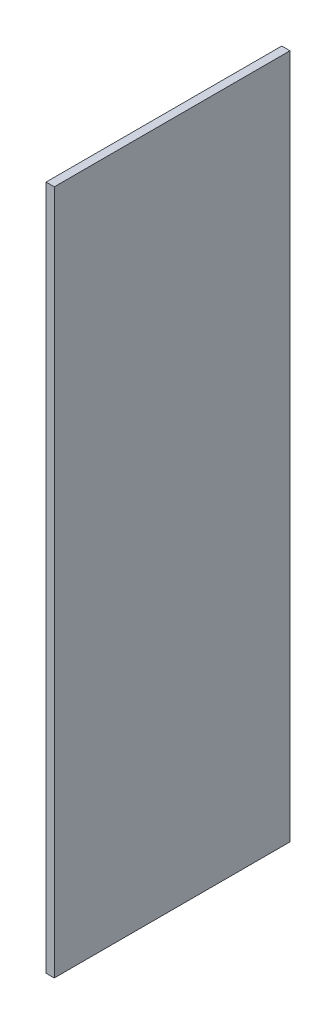
SolidWorks part; units mm, degrees
ref_plane "정면" through (0, 0, 0) normal (0, 0, 1) x (1, 0, 0)
ref_plane "윗면" through (0, 0, 0) normal (0, 1, 0) x (1, 0, 0)
ref_plane "우측면" through (0, 0, 0) normal (1, 0, 0) x (0, 0, -1)
sketch "스케치1" plane through (0, 0, 0) normal (1, 0, 0) x (0, 0, -1)
  line L1 (0, 0) -> (86, 0)
  line L2 (0, 0) -> (0, 250)
  line L3 (0, 250) -> (86, 250)
  line L4 (86, 0) -> (86, 250)
  dimension "D1" = 86
  dimension "D2" = 250
extrude "보스-돌출1" add sketch "스케치1" along normal blind 3
